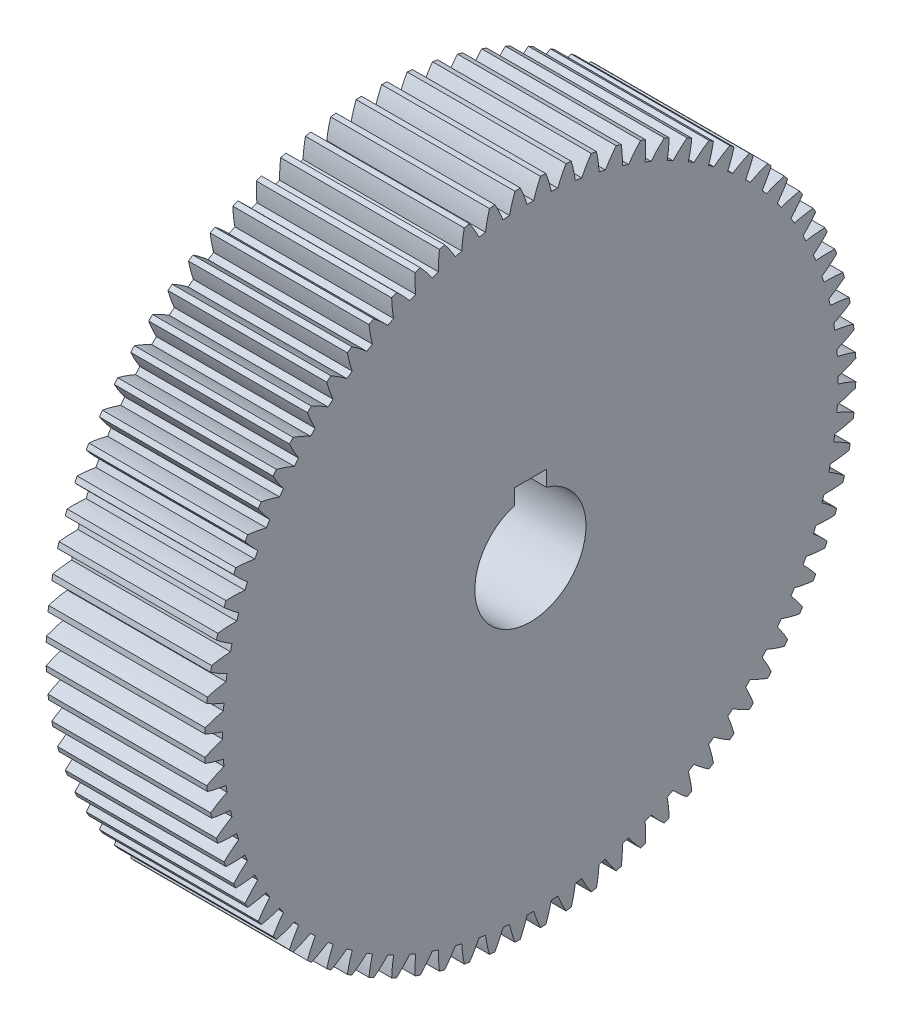
SolidWorks part; units mm, degrees
ref_plane "Plane1" through (0, 0, 0) normal (0, 0, 1) x (1, 0, 0)
ref_plane "Plane2" through (0, 0, 0) normal (0, 1, 0) x (1, 0, 0)
ref_plane "Plane3" through (0, 0, 0) normal (1, 0, 0) x (0, 0, -1)
sketch "HoldingSke" plane through (0, 0, 0) normal (0, 1, 0) x (1, 0, 0)
  line L0 (0, 0) -> (0.0868, -0.4924)
  line L1 (-15, 0) -> (100, 0) construction
  line L2 (0, 0) -> (-2.1039, 2.3779)
  line L3 (0, 0) -> (-11.863, 4.5341)
  line L4 (0, 0) -> (1.4996, 8.5048)
  line L5 (0, 0) -> (-46.8476, -17.4728)
  line L6 (0, 0) -> (-33.1585, -22.3721)
  line L7 (-2.1039, 2.3779) -> (8.6586, 51.2059)
  line L8 (-76.2, 54.61) -> (-72.9, 54.61)
  line L9 (-71.009, 38.7566) -> (-53.1078, 45.2721)
  line L10 (-76.2, 71.12) -> (104.1128, 71.12)
  line L11 (0, 0) -> (-40, 0)
  line L12 (-76.2, 101.6) -> (-76.133, 101.6)
  line L13 (24.9733, 27.94) -> (52.9518, 28.4284)
  line L14 (24.9733, 27.94) -> (24.9743, 27.94)
  line L15 (24.9733, 27.94) -> (100.4006, 29.5858)
  line L16 (-63.627, -2) -> (-12.827, -2)
  circle A0 centre (0, 0) radius 14
  circle A1 centre (0, 0) radius 37.5
  circle A2 centre (0, 0) radius 37.5
  circle A3 centre (0, 0) radius 14
  dimension "MHD" = 75
  dimension "Hub_dia" = 75
  dimension "Bore" = 28
  dimension "MBD" = 28
  dimension "Num_teeth" = 80
  dimension "Pitch" = 0.5
  dimension "Overall_len" = 50
  dimension "Show_teeth" = 80
  dimension "Thickness" = 40
  dimension "OAL" = 50.0001
  dimension "T_dim" = 3.3
  dimension "Ap" = 20
  dimension "H" = 19.05
  dimension "Pitch_radius" = 180.3128
  dimension "Width" = 40
  dimension "Backlash" = 0.067
  dimension "Addendum_fac" = 1
  dimension "Dedendum_fac" = 1.25
  dimension "Clearance_fac" = 0.25
  dimension "Dedendum_add" = 0.001
  dimension "Module" = 2
sketch "BasProSke" plane through (0, 0, 0) normal (0, 1, 0) x (1, 0, 0)
  line L0 (-10, 0) -> (60, 0) construction
  line L1 (0, 0) -> (0, 82)
  line L2 (0, 0) -> (40, 0)
  line L3 (40, 0) -> (40, 82)
  line L4 (40, 82) -> (0, 82)
  dimension "Thickness" = 40
  dimension "Diameter" = 164
revolve "Base-Revolve" add sketch "BasProSke" angle 360 about L0
sketch "TooCutSke" plane through (0, 0, 0) normal (1, 0, 0) x (0, 0, -1)
  line L1 (0, 0) -> (0, 107) construction
  line L2 (0, 0) -> (-1.6879, 79.9822) construction
  line L3 (0, 0) -> (-6.2805, 159.8503) construction
  line L4 (-1.6879, 79.9822) -> (-3.1403, 79.9251) construction
  arc A0 (0.8262, 77.4946) -> (-0.8262, 77.4946) centre (0, 0) ccw
  arc A1 (2.5557, 81.9856) -> (-2.5557, 81.9856) centre (0, 0) ccw
  circle A2 centre (0, 0) radius 80 construction
  circle A3 centre (0, 0) radius 75.1754 construction
  arc A4 (-0.8262, 77.4946) -> (-2.5557, 81.9856) centre (-31.4684, 68.2721) ccw
  arc A5 (2.5557, 81.9856) -> (0.8262, 77.4946) centre (31.4684, 68.2721) ccw
  dimension "Root_dia" = 154.998
  dimension "Overcut_dia" = 164.0508
  dimension "Pitch_dia" = 160
  dimension "Base_dia" = 150.3508
  dimension "Flank_rad" = 32
  dimension "Half_ang" = 2.25
  dimension "Half_CT" = 1.4534
extrude "ToothCut" cut sketch "TooCutSke" along normal through all
fillet "Breaks" [suppressed] radius 0.04
fillet "RootFillets" [suppressed] radius 0.501
pattern_circular "TeethCuts" count 80 every 4.5 about axis through (-10, 0, 0) along (1, 0, 0) of "ToothCut", "RootFillets", "Breaks"
sketch "HubNeaOneSke" plane through (0, 0, 0) normal (-1, 0, 0) x (0, 0, 1)
  circle A0 centre (0, 0) radius 37.5
  dimension "Diameter" = 75
extrude "HubNearOne" [suppressed] add sketch "HubNeaOneSke" along normal blind 10.0001
sketch "HubNeaBotSke" plane through (0, 0, 0) normal (-1, 0, 0) x (0, 0, 1)
  circle A0 centre (0, 0) radius 37.5
  dimension "Diameter" = 75
extrude "HubNearBoth" [suppressed] add sketch "HubNeaBotSke" along normal blind 5
ref_plane "FarPln" through (40, 0, 0) normal (1, 0, 0) x (0, 0, -1)
sketch "HubFarSke" plane through (40, 0, 0) normal (1, 0, 0) x (0, 0, -1)
  circle A0 centre (0, 0) radius 37.5
  dimension "Diameter" = 75
extrude "HubFar" [suppressed] add sketch "HubFarSke" along normal blind 5
sketch "BorSke" plane through (0, 0, 0) normal (1, 0, 0) x (0, 0, -1)
  circle A0 centre (0, 0) radius 14
  dimension "Diameter" = 28
extrude "Bore" cut sketch "BorSke" along normal mid plane 100.0001
sketch "KeySke" plane through (0, 0, 0) normal (1, 0, 0) x (0, 0, -1)
  line L0 (-4, 0) -> (-4, 17.3)
  line L1 (-4, 17.3) -> (4, 17.3)
  line L2 (4, 17.3) -> (4, 0)
  line L3 (0, 0) -> (0, 34) construction
  line L4 (-4, 0) -> (4, 0)
  dimension "Offset" = 17.3
  dimension "Width" = 8
extrude "Keyway" cut sketch "KeySke" along normal mid plane 100.0001
pattern_circular "Keyway2" [suppressed] count 2 every 90 about axis through (-10, 0, 0) along (1, 0, 0)
equation "' \"Module@HoldingSke\" = 6.35"
equation "' \"Num_teeth@HoldingSke\" = 12"
equation "' \"Ap@HoldingSke\" =  20"
equation "' \"Ap@HoldingSke\" = 20"
equation "' \"Width@HoldingSke\" = 0.5 * 25.4"
equation "' \"Hub_dia@HoldingSke\"= 1 * 25.4"
equation "' \"Hub_dia@HoldingSke\" = 1 * 25.4"
equation "' \"Overall_len@HoldingSke\" = 1.0 * 25.4"
equation "' \"Bore@HoldingSke\" = 0.75 * 25.4"
equation "' \"T_dim@HoldingSke\" = 0.1 * 25.4"
equation "' \"Width@KeySke\" = 0.25 * 25.4"
equation "' \"Show_teeth@HoldingSke\" = 13"
equation "' \"Backlash@HoldingSke\" = 0.009 * 25.4"
equation "' \"Addendum_fac@HoldingSke\" = 1.0"
equation "' \"Dedendum_fac@HoldingSke\" = 1.25"
equation "' \"Dedendum_add@HoldingSke\" = 0.00005 * 25.4"
equation "' \"Clearance_fac@HoldingSke\" = 0.25"
equation "\"Pitch@HoldingSke\" = 1 / \"Module@HoldingSke\""
equation "\"Overcut_dia@TooCutSke\" = (\"Num_teeth@HoldingSke\" + 2 * \"Addendum_fac@HoldingSke\") / \"Pitch@HoldingSke\" + 0.002 * 25.4"
equation "\"Pitch_dia@TooCutSke\" = \"Num_teeth@HoldingSke\" / \"Pitch@HoldingSke\""
equation "\"Base_dia@TooCutSke\" = \"Num_teeth@HoldingSke\" / \"Pitch@HoldingSke\" * cos((\"Ap@HoldingSke\"  * 3.14159265 / 180))"
equation "\"Root_dia@TooCutSke\" = (\"Num_teeth@HoldingSke\" + 2) / \"Pitch@HoldingSke\" - 2 * (\"Addendum_fac@HoldingSke\" + \"Dedendum_fac@HoldingSke\") / \"Pitch@HoldingSke\" - \"Dedendum_add@HoldingSke\" * 2"
equation "\"Half_ang@TooCutSke\" = 180 / \"Num_teeth@HoldingSke\""
equation "\"Half_CT@TooCutSke\" = \"Num_teeth@HoldingSke\" / \"Pitch@HoldingSke\" * sin((3.14159265 / 2 / \"Num_teeth@HoldingSke\")) / 2 - 7 * \"Backlash@HoldingSke\" / 4"
equation "\"Flank_rad@TooCutSke\" = \"Num_teeth@HoldingSke\" / \"Pitch@HoldingSke\" / 5"
equation "\"Radius@RootFillets\" = \"Clearance_fac@HoldingSke\" / \"Pitch@HoldingSke\" + \"Dedendum_add@HoldingSke\""
equation "\"Break_rad@Breaks\" = 0.02 / \"Pitch@HoldingSke\""
equation "\"Thickness@HoldingSke\" = \"Width@HoldingSke\""
equation "\"OAL@HoldingSke\" = \"Thickness@HoldingSke\""
equation "\"MHD@HoldingSke\" = (\"Num_teeth@HoldingSke\" + 2) / \"Pitch@HoldingSke\" - 2 * (\"Addendum_fac@HoldingSke\" + \"Dedendum_fac@HoldingSke\")  / \"Pitch@HoldingSke\" - \"Dedendum_add@HoldingSke\" * 2"
equation "\"MBD@HoldingSke\" = (\"Num_teeth@HoldingSke\" + 2) / \"Pitch@HoldingSke\" - 2 * (\"Addendum_fac@HoldingSke\" + \"Dedendum_fac@HoldingSke\")  / \"Pitch@HoldingSke\" - \"Dedendum_add@HoldingSke\" * 2 - 0.002 * 25.4"
equation "\"MHD@HoldingSke\" = ((sgn( \"MHD@HoldingSke\" - \"Hub_dia@HoldingSke\" )-1)*( \"MHD@HoldingSke\" - \"Hub_dia@HoldingSke\" ))/-2+ \"Hub_dia@HoldingSke\""
equation "\"MBD@HoldingSke\" = ((sgn( \"MBD@HoldingSke\" - \"Bore@HoldingSke\" )-1)*( \"MBD@HoldingSke\" - \"Bore@HoldingSke\" ))/-2+ \"Bore@HoldingSke\""
equation "\"OAL@HoldingSke\" = ((sgn( \"OAL@HoldingSke\" - \"Overall_len@HoldingSke\" )+1)*( \"OAL@HoldingSke\" - \"Overall_len@HoldingSke\" ))/2 + \"Overall_len@HoldingSke\" + 0.000002 * 25.4"
equation "\"Num_teeth@TeethCuts\" = int( \"Show_teeth@HoldingSke\" ) + 1"
equation "\"Num_teeth@TeethCuts\" = ((sgn( \"Num_teeth@TeethCuts\" - \"Num_teeth@HoldingSke\" )-1)*( \"Num_teeth@TeethCuts\" - \"Num_teeth@HoldingSke\" ))/-2+ \"Num_teeth@HoldingSke\""
equation "\"Num_teeth@TeethCuts\" = ((sgn( \"Num_teeth@TeethCuts\" - 2.0)+1)*( \"Num_teeth@TeethCuts\" - 2.0))/2 +2.0"
equation "\"Angle@TeethCuts\" = 360.0 / \"Num_teeth@HoldingSke\""
equation "\"Diameter@BasProSke\" = (\"Num_teeth@HoldingSke\" + 2 * \"Addendum_fac@HoldingSke\") / \"Pitch@HoldingSke\""
equation "\"Thickness@BasProSke\"  = \"Thickness@HoldingSke\""
equation "' \"Fillet_rad@BasProSke\" =  \"Thickness@HoldingSke\" * 0.05"
equation "' \"Fillet_rad@BasProSke\" = \"Thickness@HoldingSke\" * 0.05"
equation "\"MHD@HoldingSke\" = ((sgn( \"MHD@HoldingSke\" - \"Root_dia@TooCutSke\" )-1)*( \"MHD@HoldingSke\" - \"Root_dia@TooCutSke\" ))/-2+ \"Root_dia@TooCutSke\""
equation "\"Diameter@HubNeaOneSke\" = \"MHD@HoldingSke\""
equation "\"Length@HubNearOne\" = \"OAL@HoldingSke\" - \"Thickness@BasProSke\""
equation "\"Diameter@HubNeaBotSke\" = \"MHD@HoldingSke\""
equation "\"Length@HubNearBoth\" = ( \"OAL@HoldingSke\" - \"Thickness@BasProSke\" ) / 2.0"
equation "\"Thickness@FarPln\" = \"Thickness@BasProSke\""
equation "\"Diameter@HubFarSke\" = \"MHD@HoldingSke\""
equation "\"Length@HubFar\" = ( \"OAL@HoldingSke\" - \"Thickness@BasProSke\" ) / 2.0"
equation "\"Diameter@BorSke\" = \"MBD@HoldingSke\""
equation "\"D1@Bore\" = \"OAL@HoldingSke\" * 2.0"
equation "\"D1@Keyway\" = \"OAL@HoldingSke\" * 2.0"
equation "\"Offset@KeySke\" = \"T_dim@HoldingSke\" + \"MBD@HoldingSke\" / 2.0"
